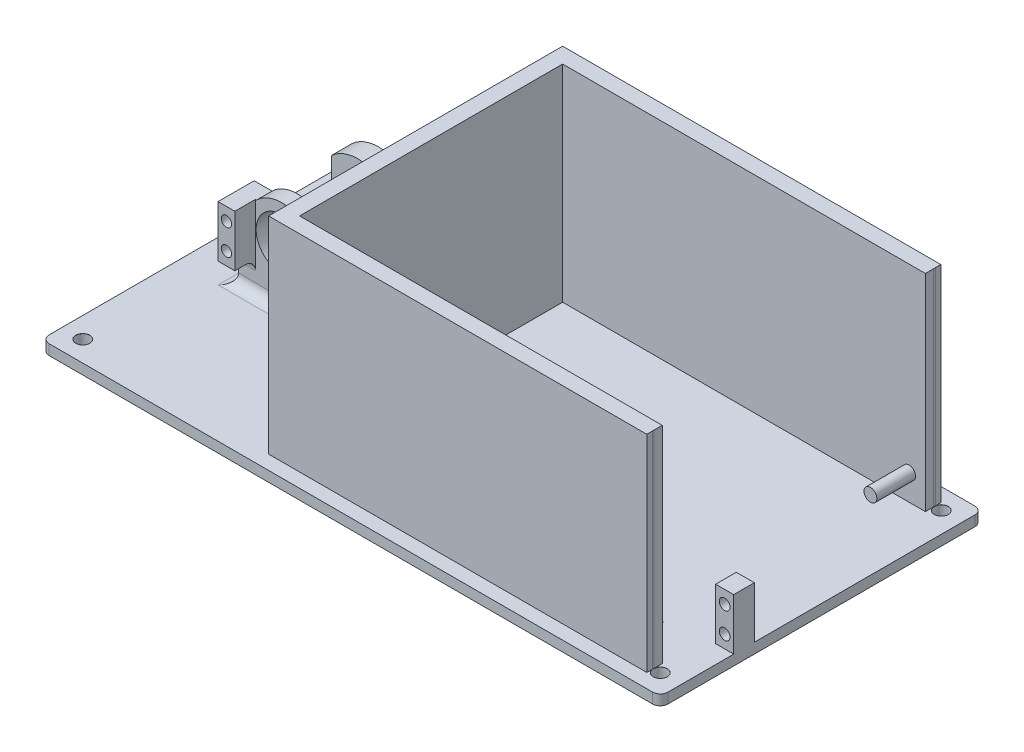
SolidWorks part; units mm, degrees
ref_plane "前视基准面" through (0, 0, 0) normal (0, 0, 1) x (1, 0, 0)
ref_plane "上视基准面" through (0, 0, 0) normal (0, 1, 0) x (1, 0, 0)
ref_plane "右视基准面" through (0, 0, 0) normal (1, 0, 0) x (0, 0, -1)
other "Configuration Table"
sketch "草图1" plane through (0, 0, 0) normal (0, 1, 0) x (1, 0, 0)
  line L1 (-120, -62.5) -> (120, -62.5)
  line L2 (-120, -62.5) -> (-120, 62.5)
  line L3 (-120, 62.5) -> (120, 62.5)
  line L4 (120, -62.5) -> (120, 62.5)
  line L5 (-120, -62.5) -> (120, 62.5) construction
  line L6 (-120, 62.5) -> (120, -62.5) construction
  point P0 (0, 0)
  dimension "D1" = 240
  dimension "D2" = 125
extrude "凸台-拉伸1" add sketch "草图1" along normal blind 4
sketch "草图2" plane through (0, 4, 0) normal (0, 1, 0) x (1, 0, 0)
  line L0 (-120, 0) -> (120, 0) construction
  line L1 (-120, 62.5) -> (-120, -62.5) construction
  line L2 (120, -62.5) -> (120, 62.5) construction
  line L3 (0, 62.5) -> (0, -62.5) construction
  line L4 (120, 62.5) -> (-120, 62.5) construction
  line L5 (-120, -62.5) -> (120, -62.5) construction
  point P12 (-112, 54.5)
  point P13 (-112, -54.5)
  point P14 (112, -54.5)
  point P15 (112, 54.5)
  dimension "D1" = 8
  dimension "D2" = 8
hole_wizard "Ø5.4 (5.4) 直径孔1" positions "草图2" profile "草图3" hole size "Ø5.4" standard "GB" end condition through all
sketch "草图3" plane through (112, 4, -54.5) normal (1, 0, 0) x (0, 0, 1)
  line L0 (0, 0) -> (0, 4)
  line L1 (0, 4) -> (2.7, 4)
  line L2 (2.7, 4) -> (2.7, 0.025)
  line L3 (2.7, 0.025) -> (2.725, 0)
  line L5 (2.725, 0) -> (0, 0)
  line L6 (-2.7, 0.025) -> (-2.725, 0) construction
  line L11 (0, -6.35) -> (0, 107.95) construction
  dimension "通孔孔直径" = 5.4
  dimension "通孔孔深度" = 4
  dimension "近端锥形沉头孔直径" = 5.45
  dimension "近端锥形沉头孔角度" = 90
fillet "圆角1" radius 3 4 edges at (120, 2, 62.5) (120, 2, -62.5) (-120, 2, 62.5) (-120, 2, -62.5)
sketch "草图4" plane through (0, 0, 0) normal (0, 0, 1) x (1, 0, 0)
  line L0 (-117, 4) -> (117, 4) construction
  line L1 (-100, 4) -> (-46, 4)
  line L2 (-100, 4) -> (-100, 36)
  line L3 (-100, 36) -> (-93.048, 36)
  line L4 (-46, 4) -> (-46, 36)
  line L5 (-120, 0) -> (-120, 4) construction
  line L7 (-73, 4) -> (-73, 36) construction
  line L9 (-83.25, 36) -> (-83.25, 4) construction
  line L10 (-100, 26) -> (-46, 26) construction
  line L12 (-73.452, 36) -> (-46, 36)
  arc A1 (-73.452, 36) -> (-93.048, 36) centre (-83.25, 26) ccw
  circle A2 centre (-83.25, 26) radius 10
  dimension "D1" = 54
  dimension "D2" = 32
  dimension "D3" = 20
extrude "凸台-拉伸2" add sketch "草图4" along normal blind 6
sketch "草图6" plane through (0, 0, 6) normal (0, 0, 1) x (1, 0, 0)
  line L0 (-100, 16) -> (-46, 16) construction
  line L1 (-100, 36) -> (-100, 4) construction
  line L2 (-46, 4) -> (-46, 36) construction
  line L3 (-100, 4) -> (-46, 4) construction
  line L4 (-73, 4) -> (-73, 36) construction
  line L5 (-46, 36) -> (-73.452, 36) construction
  line L6 (-100, 36) -> (-100, 16)
  line L7 (-93.048, 36) -> (-100, 36) construction
  line L8 (-100, 16) -> (-93.5, 16)
  line L9 (-93.5, 16) -> (-93.5, 36)
  line L10 (-93.5, 36) -> (-100, 36)
  line L11 (-52.5, 16) -> (-52.5, 36)
  line L12 (-46, 16) -> (-52.5, 16)
  line L13 (-46, 36) -> (-46, 16)
  line L14 (-52.5, 36) -> (-46, 36)
  dimension "D1" = 12
  dimension "D2" = 6.5
extrude "凸台-拉伸3" add sketch "草图6" along normal blind 8
sketch "草图7" plane through (0, 0, 14) normal (0, 0, 1) x (1, 0, 0)
  line L0 (-73, 4) -> (-73, 36) construction
  line L1 (-100, 4) -> (-46, 4) construction
  line L2 (-52.5, 36) -> (-73.452, 36) construction
  line L3 (-96.75, 16) -> (-96.75, 36) construction
  line L4 (-100, 16) -> (-93.5, 16) construction
  line L5 (-93.5, 36) -> (-100, 36) construction
  line L6 (-100, 26) -> (-93.5, 26) construction
  line L7 (-100, 36) -> (-100, 16) construction
  line L8 (-93.5, 16) -> (-93.5, 36) construction
  circle A0 centre (-96.75, 31) radius 2
  circle A1 centre (-96.75, 21) radius 2
  circle A2 centre (-49.25, 21) radius 2
  circle A3 centre (-49.25, 31) radius 2
  dimension "D1" = 4
  dimension "D2" = 5
extrude "切除-拉伸1" cut sketch "草图7" against normal up to surface (14 mm away) up to face at (-76.4167, 26, 0)
fillet "圆角2" radius 4 2 edges at (-49.25, 16, 6) (-96.75, 16, 6)
fillet "圆角3" radius 4 1 edges at (-73, 4, 6)
fillet "圆角4" radius 4 3 edges at (-73, 4, 0) (-100, 4, 5) (-46, 4, 5)
sketch "草图8" plane through (0, 0, 0) normal (0, 0, -1) x (-1, 0, 0)
  line L0 (73, 8) -> (73, 36)
  line L1 (46, 8) -> (100, 8) construction
  line L2 (46, 36) -> (73.452, 36) construction
  line L3 (93.5, 36) -> (93.5, 8)
  line L4 (93.048, 36) -> (100, 36) construction
  line L5 (100, 36) -> (100, 8) construction
  line L6 (73, 8) -> (73, 4)
  line L7 (104, 4) -> (42, 4) construction
  line L8 (73, 4) -> (93.5, 4)
  line L9 (93.5, 4) -> (93.5, 8)
  arc A0 (73, 36) -> (93.5, 36) centre (83.25, 24.8672) cw
  dimension "D1" = 6.5
extrude "凸台-拉伸4" add sketch "草图8" along normal blind 8 from offset 23.5
sketch "草图9" plane through (0, 0, -23.5) normal (0, 0, 1) x (1, 0, 0)
  circle A0 centre (-83.1168, 25.813) radius 5.5
  dimension "D1" = 11
extrude "凸台-拉伸5" add sketch "草图9" along normal blind 5
fillet "圆角5" radius 4 1 edges at (-83.25, 4, -31.5)
fillet "圆角6" radius 4 3 edges at (-73, 4, -29.5) (-83.25, 4, -23.5) (-93.5, 4, -29.5)
sketch "草图10" plane through (0, 4, 0) normal (0, 1, 0) x (1, 0, 0)
  line L0 (117, 62.5) -> (-117, 62.5) construction
  line L1 (-117, -62.5) -> (117, -62.5) construction
  line L2 (-28.367, 62.5) -> (96.633, 62.5)
  line L3 (-28.367, 62.5) -> (-28.367, -62.5)
  line L4 (-28.367, -62.5) -> (96.633, -62.5)
  line L5 (96.633, 62.5) -> (96.633, -62.5)
  line L6 (-28.367, 0) -> (96.633, 0) construction
  line L7 (34.133, 62.5) -> (34.133, -62.5) construction
  line L9 (-23.367, -57.5) -> (91.633, -57.5)
  line L10 (-23.367, -57.5) -> (-23.367, 57.5)
  line L11 (-23.367, 57.5) -> (91.633, 57.5)
  line L12 (91.633, -57.5) -> (91.633, 57.5)
  line L13 (-23.367, -57.5) -> (91.633, 57.5) construction
  line L14 (-23.367, 57.5) -> (91.633, -57.5) construction
  point P12 (34.133, 0)
  dimension "D1" = 5
ref_plane "基准面1" through (0, 64, 0) normal (0, 1, 0) x (1, 0, 0)
sketch "草图11" plane through (0, 64, 0) normal (0, 1, 0) x (1, 0, 0)
  line L0 (-23.367, -57.5) -> (91.633, 57.5) construction
  line L1 (10.133, -24) -> (58.133, -24)
  line L2 (10.133, -24) -> (10.133, 24)
  line L3 (10.133, 24) -> (58.133, 24)
  line L4 (58.133, -24) -> (58.133, 24)
  line L5 (10.133, -24) -> (15.133, -19) construction
  line L6 (10.133, 24) -> (15.133, 19) construction
  line L7 (53.133, -19) -> (58.133, -24) construction
  line L8 (53.133, 19) -> (58.133, 24) construction
  point P0 (34.133, 0)
  point P8 (34.133, 0)
  dimension "D1" = 48
ref_plane "基准面2" through (0, 124, 0) normal (0, 1, 0) x (1, 0, 0)
sketch "草图12" plane through (0, 4, 0) normal (0, 1, 0) x (1, 0, 0)
  line L0 (120, -59.5) -> (120, 59.5) construction
  line L1 (113, -26.0166) -> (120, -26.0166)
  line L2 (113, -26.0166) -> (113, -34.0166)
  line L3 (113, -34.0166) -> (120, -34.0166)
  line L4 (120, -26.0166) -> (120, -34.0166)
  line L5 (66, -26.0166) -> (66, -34.0166)
  line L6 (73, -26.0166) -> (73, -34.0166)
  line L7 (66, -34.0166) -> (73, -34.0166)
  line L8 (66, -26.0166) -> (73, -26.0166)
  dimension "D2" = 8
  dimension "D3" = 7
  dimension "D1" = 2
extrude "凸台-拉伸6" add sketch "草图12" along normal blind 20
sketch "草图13" plane through (0, 0, 34.0166) normal (0, 0, 1) x (1, 0, 0)
  line L0 (66, 14) -> (120, 14) construction
  line L1 (66, 24) -> (66, 4) construction
  line L2 (120, 24) -> (120, 4) construction
  line L3 (69.5, 24) -> (69.5, 4) construction
  line L4 (66, 24) -> (73, 24) construction
  line L5 (66, 4) -> (73, 4) construction
  line L6 (93, 14) -> (93, 4) construction
  line L7 (-117, 4) -> (117, 4) construction
  circle A0 centre (69.5, 19) radius 2.1
  circle A1 centre (69.5, 9) radius 2.1
  circle A2 centre (116.5, 9) radius 2.1
  circle A3 centre (116.5, 19) radius 2.1
  dimension "D1" = 4.2
  dimension "D2" = 5
extrude "切除-拉伸2" cut sketch "草图13" against normal up to next
sketch "草图14" plane through (0, 4, 0) normal (0, 1, 0) x (1, 0, 0)
  line L1 (96.7, -43.0166) -> (109.3, -43.0166)
  line L2 (96.7, -43.0166) -> (96.7, -51.0166)
  line L3 (96.7, -51.0166) -> (109.3, -51.0166)
  line L4 (109.3, -43.0166) -> (109.3, -51.0166)
  line L5 (96.7, -43.0166) -> (109.3, -51.0166) construction
  line L6 (96.7, -51.0166) -> (109.3, -43.0166) construction
  line L7 (120, -59.5) -> (120, -34.0166) construction
  line L8 (113, -34.0166) -> (120, -34.0166) construction
  line L9 (109.3, -57.0166) -> (-37.3786, -57.0166)
  line L10 (-37.3786, -57.0166) -> (-37.3786, -50.7641)
  line L11 (-31.3786, -51.0166) -> (96.7, -51.0166)
  line L12 (-120, 0) -> (120, 0) construction
  line L13 (-120, 59.5) -> (-120, -59.5) construction
  line L14 (120, -26.0166) -> (120, 59.5) construction
  line L15 (-37.3786, -57.0166) -> (-37.3786, 57.0166)
  line L16 (-31.3786, -51.0166) -> (-31.3786, 51.0166)
  line L17 (109.3, 57.0166) -> (-37.3786, 57.0166)
  line L18 (-31.3786, 51.0166) -> (96.7, 51.0166)
  line L19 (95.4609, 51.0166) -> (109.3, 51.0166)
  line L20 (109.3, 51.0166) -> (109.3, 57.0166)
  line L21 (109.3, -51.0166) -> (109.3, -57.0166)
  circle A1 centre (112, -54.5) radius 2.7 construction
  point P0 (103, -47.0166)
  point P30 (-37.3786, 0)
  point P31 (-31.3786, 0)
  circle M15 centre (112, -54.5) radius 2.725
  circle M16 centre (112, 54.5) radius 2.725
  dimension "D1" = 17
  dimension "D2" = 9
  dimension "D3" = 17
  dimension "D4" = 6
  dimension "D5" = 6
extrude "凸台-拉伸7" add sketch "草图14" along normal blind 80 contours L21 L3 L11 L16 L18 L19 L20 L17 L15 L10 L9 M16 M15
sketch "草图15" plane through (0, 0, 51.0166) normal (0, 0, -1) x (-1, 0, 0)
  line L0 (-120, 24) -> (-120, 4) construction
  line L1 (-109.3, 4) -> (37.3786, 4) construction
  circle A0 centre (-103, 14) radius 2.5
  dimension "D3" = 5
  dimension "D1" = 17
  dimension "D2" = 10
extrude "凸台-拉伸8" add sketch "草图15" along normal blind 4
sketch "草图17" plane through (0, 0, -51.0166) normal (0, 0, 1) x (1, 0, 0)
  line L1 (-31.3786, 4) -> (109.3, 4) construction
  line L2 (120, 4) -> (120, 0) construction
  circle A0 centre (103, 14) radius 2.5
  point P2 (0, 0)
  dimension "D3" = 5
  dimension "D1" = 17
  dimension "D2" = 10
extrude "凸台-拉伸9" add sketch "草图17" along normal blind 15
